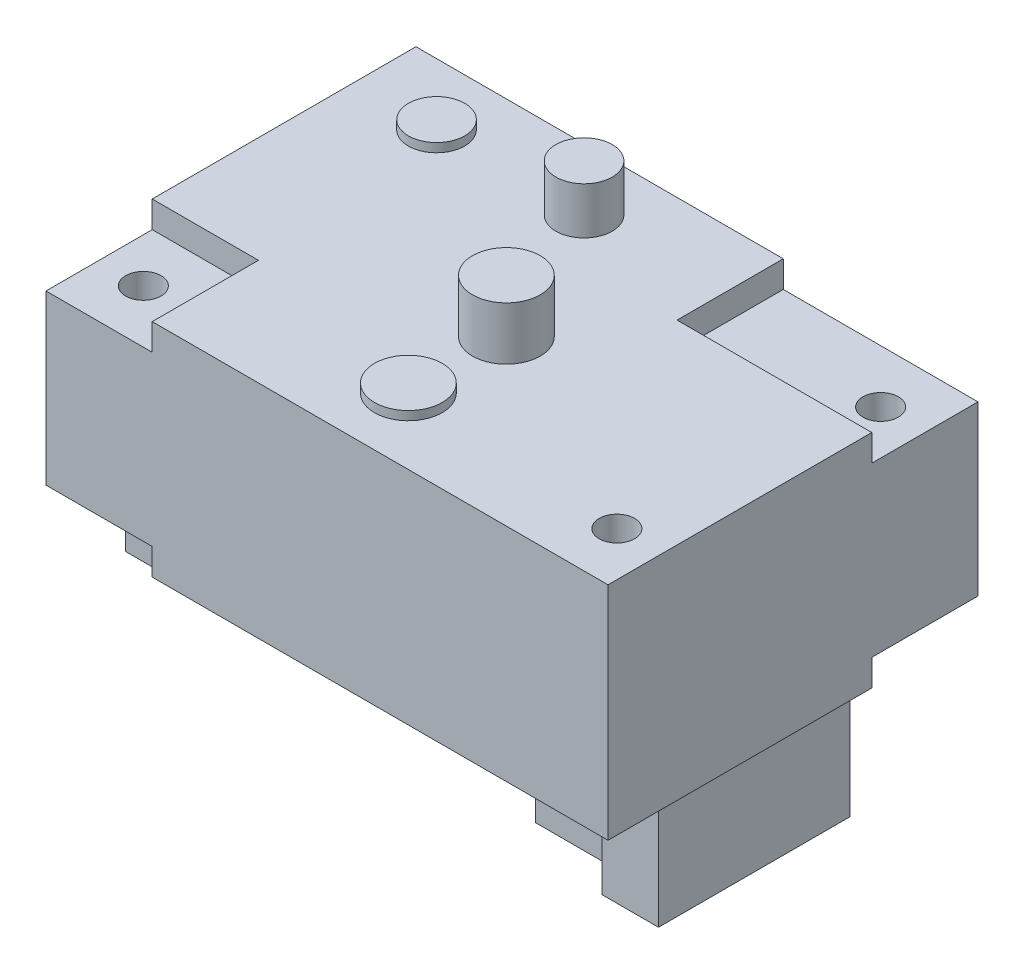
SolidWorks part; units mm, degrees
ref_plane "前视基准面" through (0, 0, 0) normal (0, 0, 1) x (1, 0, 0)
ref_plane "上视基准面" through (0, 0, 0) normal (0, 1, 0) x (1, 0, 0)
ref_plane "右视基准面" through (0, 0, 0) normal (1, 0, 0) x (0, 0, -1)
ref_plane "基准面4" through (0, 0, 6.9677) normal (0, 0, -1) x (-1, 0, 0)
sketch "草图1" plane through (0, 0, 6.9677) normal (0, 0, -1) x (-1, 0, 0)
  line L0 (-12.4763, 24.9999) -> (-9.2929, 24.9999)
  line L1 (-9.2929, 24.9999) -> (-9.2929, 25.9999)
  line L2 (-9.2929, 25.9999) -> (-12.4763, 25.9999)
  line L3 (-12.4763, 25.9999) -> (-12.4763, 24.9999)
  line L4 (-9.2929, 24.9999) -> (-9.2929, 25.9999) construction
  dimension "D1" = 1
revolve "旋转1" add sketch "草图1" angle 360 about L4
ref_plane "基准面5" through (0, 24.9999, 0) normal (0, 1, 0) x (1, 0, 0)
sketch "草图2" plane through (0, 24.9999, 0) normal (0, 1, 0) x (1, 0, 0)
  line L0 (12.4763, -3.7842) -> (0, -3.7842)
  line L1 (0, -3.7842) -> (0, -41.7999)
  line L2 (0, -41.7999) -> (12.4763, -41.7999)
  line L3 (12.4763, -41.7999) -> (12.4763, -3.7842)
extrude "凸台-拉伸1" add sketch "草图2" against normal blind 24.9999
sketch "草图3" plane through (0, 0, 3.7842) normal (0, 0, -1) x (-1, 0, 0)
  line L0 (-12.4763, 24.9999) -> (0, 24.9999)
  line L1 (0, 24.9999) -> (0, 0)
  line L2 (0, 0) -> (-12.4763, 0)
  line L3 (-12.4763, 0) -> (-12.4763, 24.9999)
extrude "凸台-拉伸2" add sketch "草图3" along normal blind 3.7842
sketch "草图4" plane through (12.4763, 0, 0) normal (1, 0, 0) x (0, 0, -1)
  line L0 (0, 0) -> (-41.7999, 0)
  line L1 (-41.7999, 0) -> (-41.7999, 24.9999)
  line L2 (-41.7999, 24.9999) -> (0, 24.9999)
  line L3 (0, 24.9999) -> (0, 0)
extrude "凸台-拉伸3" add sketch "草图4" along normal blind 51.0236
ref_plane "基准面6" through (0, 25.9999, 0) normal (0, -1, 0) x (1, 0, 0)
sketch "草图5" plane through (0, 25.9999, 0) normal (0, -1, 0) x (1, 0, 0)
  line L0 (63.4999, 41.7999) -> (0, 41.7999)
  line L1 (0, 41.7999) -> (0, 0)
  line L2 (0, 0) -> (63.4999, 0)
  line L3 (63.4999, 0) -> (63.4999, 41.7999)
sketch "草图6" plane through (0, 0, 0) normal (0, -1, 0) x (1, 0, 0)
  line L0 (0, 0) -> (0, 32.7999)
  line L1 (0, 32.7999) -> (21.5, 32.7999)
  line L2 (21.5, 32.7999) -> (21.5, 0)
  line L3 (21.5, 0) -> (0, 0)
extrude "凸台-拉伸5" add sketch "草图6" along normal blind 8
sketch "草图7" plane through (0, 0, 41.7999) normal (0, 0, 1) x (1, 0, 0)
  line L0 (0, 0) -> (12, 0)
  line L1 (12, 0) -> (12, 3)
  line L2 (12, 3) -> (0, 3)
  line L3 (0, 3) -> (0, 0)
extrude "切除-拉伸1" cut sketch "草图7" against normal blind 9
ref_plane "基准面7" through (0, 0, 32.7999) normal (0, 0, 1) x (1, 0, 0)
ref_plane "基准面8" through (0, 0, 29.7999) normal (0, 0, -1) x (-1, 0, 0)
sketch "草图9" plane through (0, 0, 29.7999) normal (0, 0, -1) x (-1, 0, 0)
  line L0 (0, 3) -> (-12, 3)
  line L1 (-12, 3) -> (-12, 0)
  line L2 (-12, 0) -> (0, 0)
  line L3 (0, 0) -> (0, 3)
extrude "切除-拉伸2" cut sketch "草图9" against normal up to surface up to plane "基准面7"
sketch "草图10" plane through (0, 0, 0) normal (0, -1, 0) x (1, 0, 0)
  line L0 (61.8644, 34.461) -> (61.8644, 12.8143)
  line L1 (61.8644, 12.8143) -> (55.4977, 12.8143)
  line L2 (55.4977, 12.8143) -> (55.4977, 34.461)
  line L3 (55.4977, 34.461) -> (61.8644, 34.461)
extrude "凸台-拉伸6" add sketch "草图10" along normal blind 13
sketch "草图11" plane through (0, 0, 41.7999) normal (0, 0, 1) x (1, 0, 0)
  line L0 (0, 22) -> (12, 22)
  line L1 (12, 22) -> (12, 24.9999)
  line L2 (12, 24.9999) -> (0, 24.9999)
  line L3 (0, 24.9999) -> (0, 22)
extrude "切除-拉伸3" cut sketch "草图11" against normal blind 12
sketch "草图12" plane through (63.4999, 0, 0) normal (1, 0, 0) x (0, 0, -1)
  line L0 (-12, 22) -> (0, 22)
  line L1 (0, 22) -> (0, 24.9999)
  line L2 (0, 24.9999) -> (-12, 24.9999)
  line L3 (-12, 24.9999) -> (-12, 22)
extrude "切除-拉伸4" cut sketch "草图12" against normal blind 22
sketch "草图13" plane through (63.4999, 0, 0) normal (1, 0, 0) x (0, 0, -1)
  line L0 (0, 3) -> (-12, 3)
  line L1 (-12, 3) -> (-12, 0)
  line L2 (-12, 0) -> (0, 0)
  line L3 (0, 0) -> (0, 3)
extrude "切除-拉伸5" cut sketch "草图13" against normal blind 12
sketch "草图14" plane through (0, 0, 0) normal (0, -1, 0) x (1, 0, 0)
  line L0 (54.3599, 32.1731) -> (54.3599, 12.8113)
  line L1 (54.3599, 12.8113) -> (45.6981, 12.8113)
  line L2 (45.6981, 12.8113) -> (45.6981, 32.1731)
  line L3 (45.6981, 32.1731) -> (54.3599, 32.1731)
extrude "凸台-拉伸7" add sketch "草图14" along normal blind 12
ref_plane "基准面9" through (0, 0, 34.3254) normal (0, 0, -1) x (-1, 0, 0)
sketch "草图15" plane through (0, 0, 34.3254) normal (0, 0, -1) x (-1, 0, 0)
  line L0 (-37.2961, 24.9999) -> (-33.4679, 24.9999)
  line L1 (-33.4679, 24.9999) -> (-33.4679, 25.9999)
  line L2 (-33.4679, 25.9999) -> (-37.2961, 25.9999)
  line L3 (-37.2961, 25.9999) -> (-37.2961, 24.9999)
  line L4 (-33.4679, 24.9999) -> (-33.4679, 25.9999) construction
revolve "旋转2" add sketch "草图15" angle 360 about L4
ref_plane "基准面10" through (0, 0, 23.2542) normal (0, 0, -1) x (-1, 0, 0)
sketch "草图16" plane through (0, 0, 23.2542) normal (0, 0, -1) x (-1, 0, 0)
  line L0 (-37.2961, 24.9999) -> (-33.4679, 24.9999)
  line L1 (-33.4679, 24.9999) -> (-33.4679, 30.9999)
  line L2 (-33.4679, 30.9999) -> (-37.2961, 30.9999)
  line L3 (-37.2961, 30.9999) -> (-37.2961, 24.9999)
  line L4 (-33.4679, 24.9999) -> (-33.4679, 30.9999) construction
  dimension "D1" = 6
revolve "旋转3" add sketch "草图16" angle 360 about L4
sketch "草图17" plane through (0, 0, 6.9677) normal (0, 0, -1) x (-1, 0, 0)
  line L0 (-29.1442, 24.9999) -> (-25.9607, 24.9999)
  line L1 (-25.9607, 24.9999) -> (-25.9607, 30.2999)
  line L2 (-25.9607, 30.2999) -> (-29.1442, 30.2999)
  line L3 (-29.1442, 30.2999) -> (-29.1442, 24.9999)
  line L4 (-25.9607, 24.9999) -> (-25.9607, 30.2999) construction
  dimension "D1" = 5.3
revolve "旋转4" add sketch "草图17" angle 360 about L4
hole_wizard "M3.5 间隙孔4" positions "草图25" profile "草图24" hole size "M3.5" standard "ANSI Metric"
sketch "草图25" plane through (0, 24.9999, 0) normal (0, 1, 0) x (1, 0, 0)
  point P0 (58.4999, -35.7999)
sketch "草图24" plane through (58.4999, 24.9999, 35.7999) normal (1, 0, 0) x (0, 0, 1)
  line L0 (0, 0) -> (0, 22)
  line L1 (0, 22) -> (2, 22)
  line L2 (2, 22) -> (2, 0)
  line L5 (2, 0) -> (0, 0)
  line L10 (0, 22) -> (-2, 22) construction
  line L11 (0, -6.35) -> (0, 107.95) construction
  dimension "孔直径" = 4
  dimension "孔深度" = 22
  dimension "导头角度" = 180
hole_wizard "孔1" positions "草图27" profile "草图26" legacy
sketch "草图27" plane through (21.5, 0, 0) normal (1, 0, 0) x (0, 0, -1)
  point P0 (-16.501, -3.8751)
  point P1 (-21.6456, -3.8751)
  point P2 (-26.07, -3.8751)
  point P3 (-30.3914, -3.8751)
  point P4 (-11.8708, -3.8751)
  point P5 (-7.858, -3.8751)
  point P6 (-3.2278, -3.8751)
sketch "草图26" plane through (21.5, -3.8751, 16.501) normal (0, 1, 0) x (0, 0, -1)
  line L0 (0, 0) -> (0, 21.5)
  line L1 (0, 21.5) -> (1.3376, 21.5)
  line L2 (1.3376, 21.5) -> (1.3376, 0)
  line L3 (1.3376, 0) -> (0, 0)
  line L4 (0, 110) -> (0, -10) construction
  dimension "直径" = 2.6752
  dimension "深度" = 21.5
hole_wizard "M3.5 间隙孔5" positions "草图29" profile "草图28" hole size "M3.5" standard "ANSI Metric"
sketch "草图29" plane through (0, 22, 0) normal (0, 1, 0) x (1, 0, 0)
  point P0 (58.4999, -6)
  point P1 (5, -35.7999)
sketch "草图28" plane through (58.4999, 22, 6) normal (1, 0, 0) x (0, 0, 1)
  line L0 (0, 0) -> (0, 34.9999)
  line L1 (0, 34.9999) -> (2, 34.9999)
  line L2 (2, 34.9999) -> (2, 0)
  line L5 (2, 0) -> (0, 0)
  line L11 (0, -6.35) -> (0, 107.95) construction
  dimension "通孔孔直径" = 4
  dimension "通孔孔深度" = 34.9999
